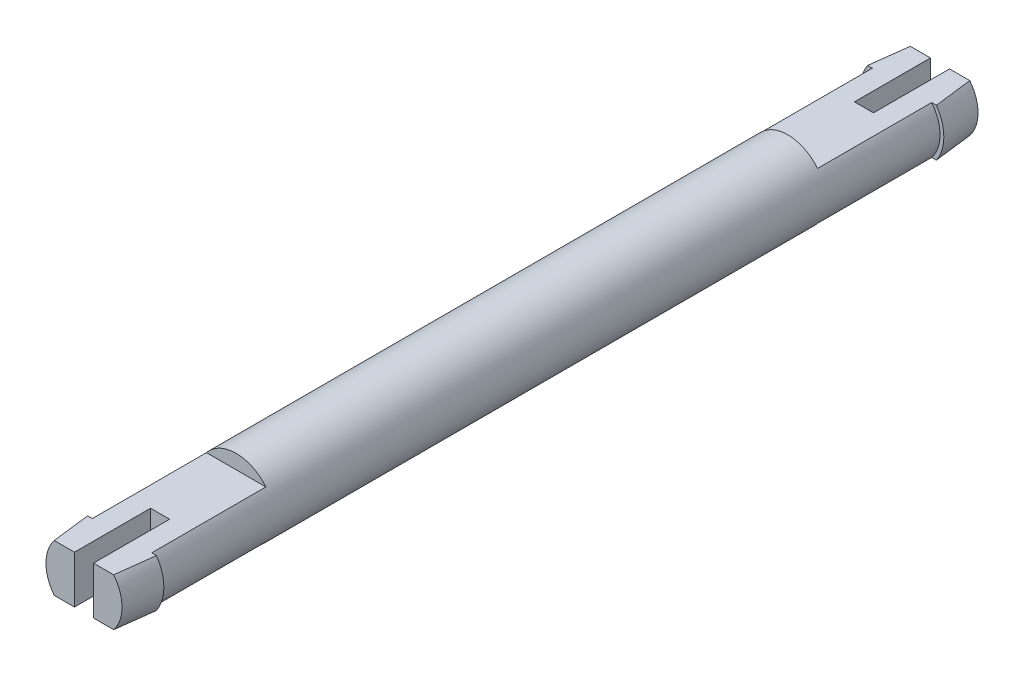
SolidWorks part; units mm, degrees
ref_plane "前视基准面" through (0, 0, 0) normal (0, 0, 1) x (1, 0, 0)
ref_plane "上视基准面" through (0, 0, 0) normal (0, 1, 0) x (1, 0, 0)
ref_plane "右视基准面" through (0, 0, 0) normal (1, 0, 0) x (0, 0, -1)
sketch "草图1" plane through (0, 0, 0) normal (0, 0, 1) x (1, 0, 0)
  circle A0 centre (0, 0) radius 2
extrude "凸台-拉伸1" add sketch "草图1" against normal blind 45
sketch "草图2" plane through (0, 0, 0) normal (0, 1, 0) x (1, 0, 0)
  line L0 (0, 0) -> (0, 2)
  line L1 (0, 2) -> (2.2, 2)
  line L2 (0, 0) -> (2, 0)
  line L3 (2, 0) -> (2.2, 2)
  dimension "D1" = 2.2
  dimension "D2" = 2
revolve "旋转1" add sketch "草图2" angle 360 about L0
sketch "草图3" plane through (0, 0, 0) normal (0, 0, 1) x (1, 0, 0)
  line L0 (-2.1, 1.25) -> (-2.1, 2.25)
  line L1 (-2.1, 1.25) -> (2.1, 1.25)
  line L2 (2.1, 1.25) -> (2.1, 2.25)
  line L3 (-2.1, -1.25) -> (2.1, -1.25)
  line L5 (-2.1, -2.25) -> (2.1, -2.25)
  line L6 (-2.1, -2.25) -> (-2.1, -1.25)
  line L7 (-2.1, 2.25) -> (2.1, 2.25)
  line L8 (2.1, -2.25) -> (2.1, -1.25)
  dimension "D1" = 1.25
  dimension "D2" = 1.25
  dimension "D3" = 1
  dimension "D4" = 1
extrude "切除-拉伸1" cut sketch "草图3" against normal blind 8
sketch "草图4" plane through (0, -1.25, 0) normal (0, -1, 0) x (1, 0, 0)
  line L0 (1.5612, 0) -> (-1.5612, 0) construction
  line L1 (-0.5, 0) -> (0.5, 0)
  line L2 (-0.5, 0) -> (-0.5, -4)
  line L3 (-0.5, -4) -> (0.5, -4)
  line L4 (0.5, 0) -> (0.5, -4)
extrude "切除-拉伸2" cut sketch "草图4" against normal up to next
sketch "草图5" plane through (0, 0, 0) normal (0, 1, 0) x (1, 0, 0)
  line L0 (0, 45) -> (0, 43)
  line L1 (2, 45) -> (-2, 45) construction
  line L2 (0, 43) -> (2.2, 43)
  line L3 (2.2, 43) -> (2, 45)
  line L4 (2, 45) -> (0, 45)
  line L5 (0, 58.1377) -> (0, 60.3241) construction
  dimension "D1" = 2.2
  dimension "D2" = 2
revolve "旋转2" add sketch "草图5" angle 360 about L5
sketch "草图6" plane through (0, 0, -45) normal (0, 0, -1) x (-1, 0, 0)
  line L1 (-2.1, 1.25) -> (2.1, 1.25)
  line L2 (-2.1, 1.25) -> (-2.1, 2.25)
  line L3 (-2.1, 2.25) -> (2.1, 2.25)
  line L4 (2.1, 1.25) -> (2.1, 2.25)
  line L5 (-2.1, -1.25) -> (2.1, -1.25)
  line L6 (-2.1, -1.25) -> (-2.1, -2.25)
  line L7 (-2.1, -2.25) -> (2.1, -2.25)
  line L8 (2.1, -1.25) -> (2.1, -2.25)
  dimension "D1" = 1.25
  dimension "D2" = 1.25
  dimension "D3" = 1
  dimension "D4" = 1
extrude "切除-拉伸3" cut sketch "草图6" against normal blind 8
sketch "草图7" plane through (0, 1.25, 0) normal (0, 1, 0) x (1, 0, 0)
  line L0 (0, 45) -> (0, 41) construction
  line L1 (-1.5612, 45) -> (1.5612, 45) construction
  line L2 (-0.5, 41) -> (0.5, 41)
  line L3 (0.5, 41) -> (0.5, 45)
  line L4 (0.5, 45) -> (-0.5, 45)
  line L5 (-0.5, 41) -> (-0.5, 45)
  dimension "D1" = 4
  dimension "D2" = 0.5
extrude "切除-拉伸4" cut sketch "草图7" against normal through all
